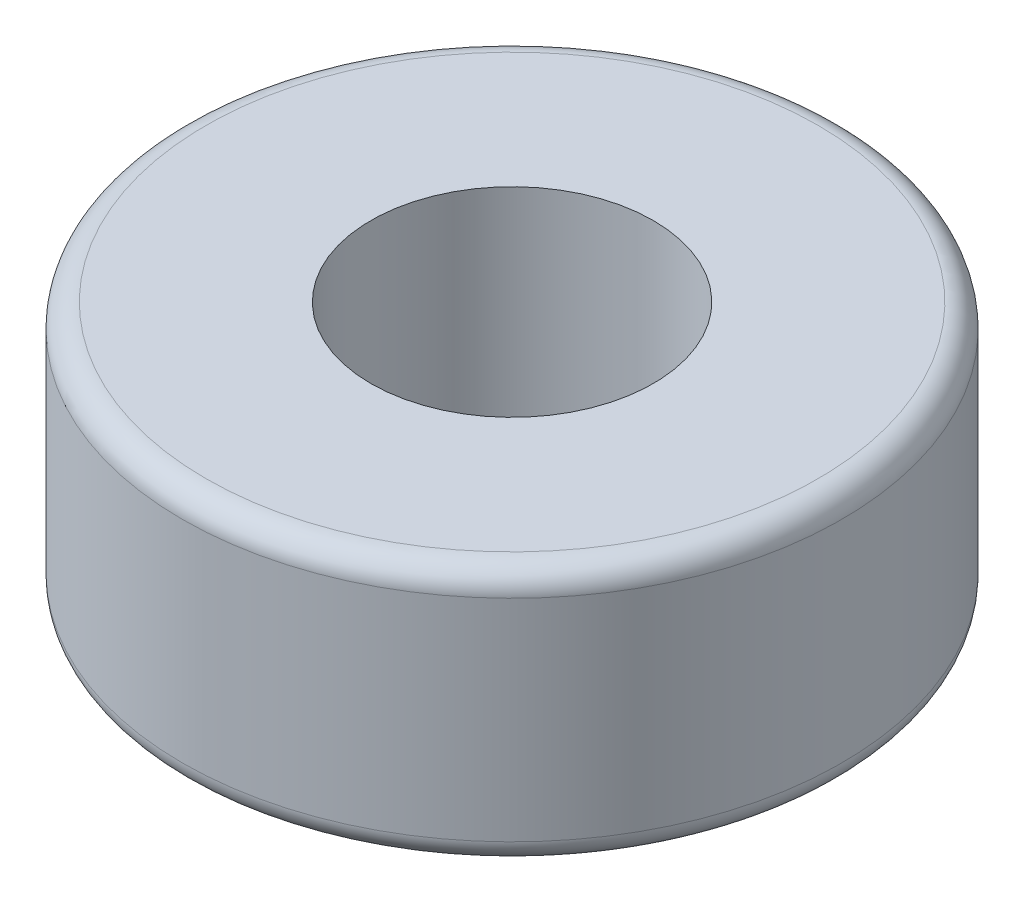
SolidWorks part; units mm, degrees
material "Acier allié"
ref_plane "Face" through (0, 0, 0) normal (0, 0, 1) x (1, 0, 0)
ref_plane "Dessus" through (0, 0, 0) normal (0, 1, 0) x (1, 0, 0)
ref_plane "Droite" through (0, 0, 0) normal (1, 0, 0) x (0, 0, -1)
sketch "Esquisse1" plane through (0, 0, 0) normal (0, 1, 0) x (1, 0, 0)
  circle A0 centre (0, 0) radius 11.1125
  circle A1 centre (0, 0) radius 4.7625
  dimension "D1" = 9.525
  dimension "D2" = 22.225
extrude "Boss.-Extru.1" add sketch "Esquisse1" along normal mid plane 8.6995
fillet "Congé1" radius 0.7937 2 edges at (0, -4.3498, 11.1125) (0, 4.3498, 11.1125)
